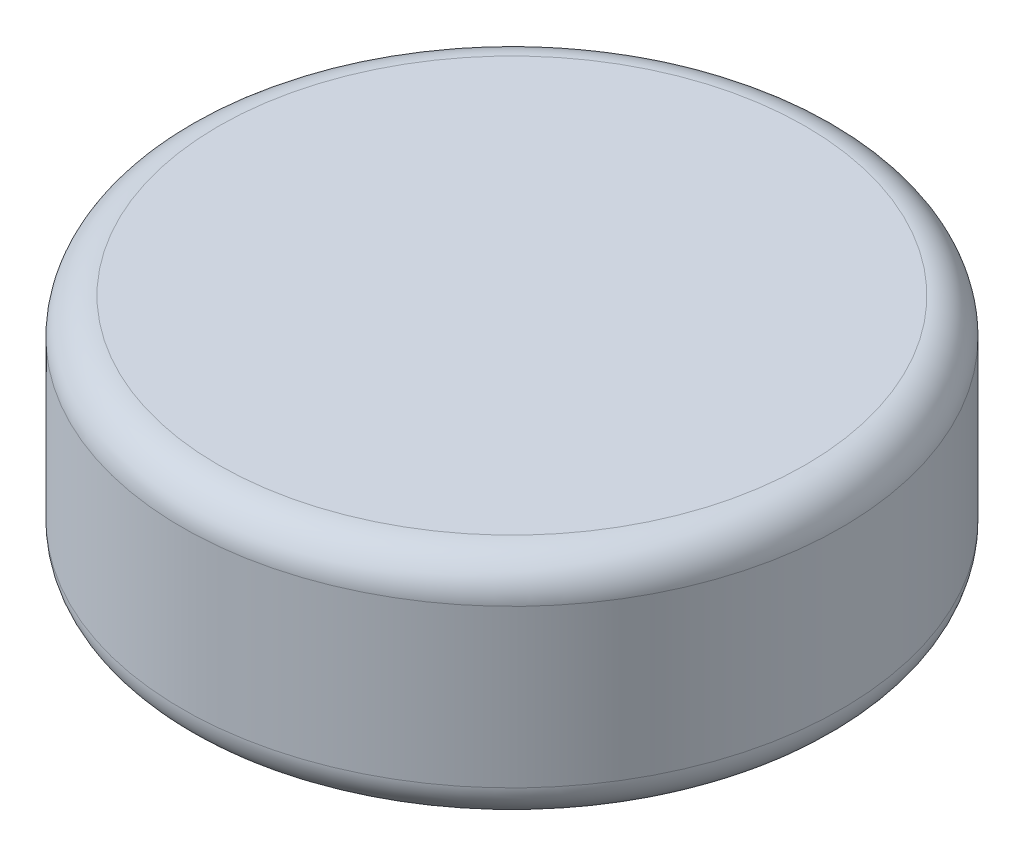
SolidWorks part; units mm, degrees
ref_plane "Front Plane" through (0, 0, 0) normal (0, 0, 1) x (1, 0, 0)
ref_plane "Top Plane" through (0, 0, 0) normal (0, 1, 0) x (1, 0, 0)
ref_plane "Right Plane" through (0, 0, 0) normal (1, 0, 0) x (0, 0, -1)
sketch "Sketch1" plane through (0, 0, 0) normal (0, 0, 1) x (1, 0, 0)
  line L0 (0, 0) -> (0, 12.6994)
  line L1 (0, 0) -> (16.2369, 0)
  line L2 (18.2369, 2) -> (18.2369, 10.6994)
  line L3 (16.2369, 12.6994) -> (0, 12.6994)
  arc A0 (16.2369, 0) -> (18.2369, 2) centre (16.2369, 2) ccw
  arc A1 (18.2369, 10.6994) -> (16.2369, 12.6994) centre (16.2369, 10.6994) ccw
  dimension "D1" = 2
revolve "Revolve1" add sketch "Sketch1" angle 360 about L0
